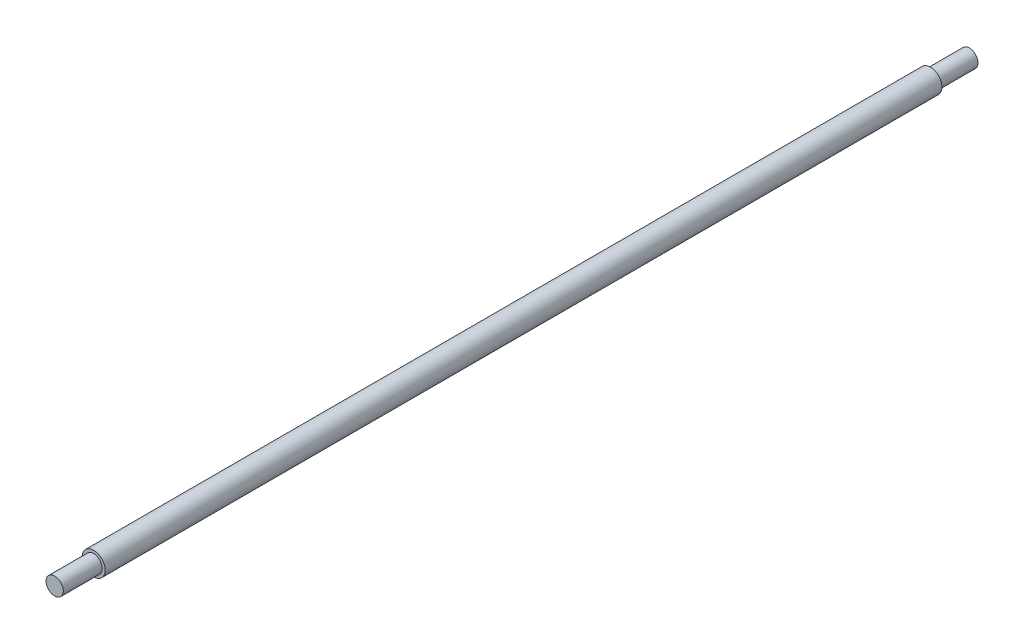
SolidWorks part; units mm, degrees
material "Brass"
ref_plane "Front Plane" through (0, 0, 0) normal (0, 0, 1) x (1, 0, 0)
ref_plane "Top Plane" through (0, 0, 0) normal (0, 1, 0) x (1, 0, 0)
ref_plane "Right Plane" through (0, 0, 0) normal (1, 0, 0) x (0, 0, -1)
sketch "Sketch1" plane through (0, 0, 0) normal (1, 0, 0) x (0, 0, -1)
  line L0 (158.5, 0) -> (-158.5, 0)
  line L1 (-158.5, 0) -> (-158.5, 3)
  line L2 (-158.5, 3) -> (-145, 3)
  line L3 (-145, 3) -> (-145, 4)
  line L4 (-145, 4) -> (145, 4)
  line L5 (145, 4) -> (145, 3)
  line L6 (145, 3) -> (158.5, 3)
  line L7 (158.5, 3) -> (158.5, 0)
  point P4 (0, 0)
  dimension "D1" = 317
  dimension "D2" = 13.5
  dimension "D3" = 13.5
  dimension "D4" = 3
  dimension "D5" = 4
  dimension "D6" = 3
revolve "Revolve1" add sketch "Sketch1" angle 360 about L0
cosmetic thread "Cosmetic Thread1" parameters "D2"=4.891
cosmetic thread "Cosmetic Thread2" parameters "D2"=4.891
